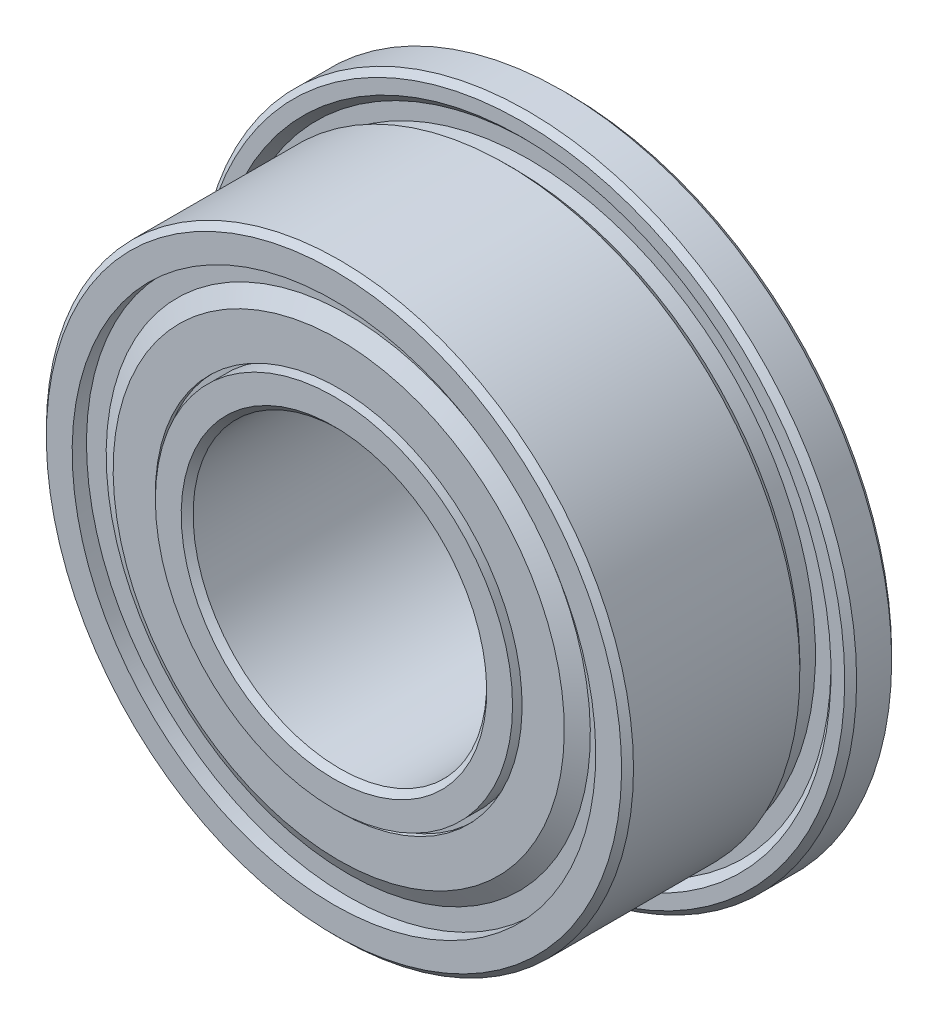
SolidWorks part; units mm, degrees
ref_plane "Front Plane" through (0, 0, 0) normal (0, 0, 1) x (1, 0, 0)
ref_plane "Top Plane" through (0, 0, 0) normal (0, 1, 0) x (1, 0, 0)
ref_plane "Right Plane" through (0, 0, 0) normal (1, 0, 0) x (0, 0, -1)
sketch "Sketch1" plane through (0, 0, 0) normal (1, 0, 0) x (0, 0, -1)
  line L0 (0, 5) -> (0, -5) construction
  line L1 (-2, 5) -> (2, 5) construction
  line L2 (0, 0) -> (2, 0) construction
  line L3 (2, 5.6) -> (2, -5.6) construction
  line L4 (2, -5.6) -> (1.2, -5.6) construction
  line L5 (2, 2.5) -> (0, 2.5) construction
  line L6 (2, 2.5) -> (2, -2.5) construction
  dimension "OD" = 10
  dimension "Width" = 4
  dimension "Flange Thickness" = 0.8
  dimension "ID" = 5
  dimension "Flange OD" = 11.2
sketch "Sketch2" plane through (0, 0, 0) normal (1, 0, 0) x (0, 0, -1)
  line L0 (2, 5.6) -> (1.2, 5.6)
  line L1 (1.2, 5.6) -> (1.2, 5.2652)
  line L2 (0.9348, 5) -> (-2, 5)
  line L3 (-2, 5) -> (-2, 4.1875)
  line L4 (-2, 4.1875) -> (-0.4106, 4.1875)
  line L5 (2, 5.6) -> (2, -5.6) construction
  line L6 (2, 4.1875) -> (2, 5.6)
  line L7 (2, 2.5) -> (-2, 2.5)
  line L8 (-2, 2.5) -> (-2, 3.3125)
  line L9 (-2, 3.3125) -> (-0.4106, 3.3125)
  line L10 (2, 3.3125) -> (2, 2.5)
  line L11 (0, 5) -> (0, 2.5) construction
  line L12 (-0.6, 3.75) -> (0.6, 3.75) construction
  line L13 (0.4106, 4.1875) -> (2, 4.1875)
  line L14 (0.4106, 3.3125) -> (2, 3.3125)
  line L15 (1.2, 5.2652) -> (1.3326, 5.1326)
  line L16 (1.3326, 5.1326) -> (1.3326, 4.8674)
  line L17 (1.3326, 4.8674) -> (1.0674, 4.8674)
  line L18 (1.0674, 4.8674) -> (0.9348, 5)
  line L19 (1.2, 5) -> (1.3326, 4.8674) construction
  line L20 (1.3326, 5.1326) -> (1.0674, 4.8674) construction
  line L21 (0.9348, 5) -> (1.2, 5) construction
  line L22 (1.2, 5) -> (1.2, 5.2652) construction
  line L23 (-2, 0) -> (2, 0) construction
  circle A0 centre (0, 3.75) radius 0.6 construction
  arc A1 (-0.4106, 4.1875) -> (0.4106, 4.1875) centre (0, 3.75) cw
  arc A2 (-0.4106, 3.3125) -> (0.4106, 3.3125) centre (0, 3.75) ccw
  dimension "Ball Dia." = 1.2
  dimension "D2" = 135
  dimension "D3" = 0.375
  dimension "Race Thikness" = 0.8125
  dimension "D4" = 0.875
revolve "Revolve1" add sketch "Sketch2" angle 360 about L2
fillet "Fillet1" radius 0.1016 3 edges at (0, -5.6, -2) (0, -5.6, -1.2) (0, -5, 2) profile chamfer
sketch "Sketch3" plane through (0, 0, 0) normal (0, 0, 1) x (1, 0, 0)
  line L0 (-2.5, 0) -> (2.5, 0) construction
  line L1 (-5, 0) -> (5, 0) construction
  point P5 (0, 0)
  dimension "ID2" = 5
  dimension "OD2" = 10
fillet "Fillet2" radius 0.1016 2 edges at (0, -2.5, -2) (0, -2.5, 2) profile chamfer
sketch "Sketch7" plane through (0, 0, 0) normal (0, 0, 1) x (1, 0, 0)
  line L0 (0, 4.35) -> (0, 3.15)
  line L1 (0, 5.6) -> (0, -5.6) construction
  line L2 (-0.7051, 4.35) -> (0, 0) construction
  line L3 (0, 0) -> (0.7051, 4.35) construction
  line L4 (0.7051, 4.35) -> (-0.7051, 4.35) construction
  circle A0 centre (0, 3.75) radius 0.6 construction
  circle A1 centre (0, 0) radius 4.35 construction
  circle A2 centre (0, 0) radius 3.15 construction
  arc A4 (0, 4.35) -> (0, 3.15) centre (0, 3.75) ccw
  dimension "D1" = 18.414
revolve "Revolve3" add sketch "Sketch7" angle 360 about L0
pattern_circular "CirPattern3" count 16 over 360 about axis through (0, 0, 0) along (0, 0, 1) of bodies 107
sketch "Sketch8" plane through (0, 0, 0) normal (1, 0, 0) x (0, 0, -1)
  line L1 (-2, 4.1875) -> (-1.675, 4.1875)
  line L2 (-2, 4.1875) -> (-2, 4.4583)
  line L3 (-2, 4.4583) -> (-1.675, 4.4583)
  line L4 (-1.675, 4.1875) -> (-1.675, 4.4583)
  line L5 (2, 4.1875) -> (1.675, 4.1875)
  line L6 (2, 4.1875) -> (2, 4.4583)
  line L7 (2, 4.4583) -> (1.675, 4.4583)
  line L8 (1.675, 4.1875) -> (1.675, 4.4583)
  line L9 (2, 3.3125) -> (1.675, 3.3125)
  line L10 (2, 3.3125) -> (2, 3.0417)
  line L11 (2, 3.0417) -> (1.675, 3.0417)
  line L12 (1.675, 3.3125) -> (1.675, 3.0417)
  line L13 (-2, 3.3125) -> (-1.675, 3.3125)
  line L14 (-2, 3.3125) -> (-2, 3.0417)
  line L15 (-2, 3.0417) -> (-1.675, 3.0417)
  line L16 (-1.675, 3.3125) -> (-1.675, 3.0417)
  dimension "D1" = 0.2708
  dimension "D2" = 0.325
revolve "Cut-Revolve1" cut sketch "Sketch8" angle 360 about L2
sketch "Sketch9" plane through (0, 0, 0) normal (1, 0, 0) x (0, 0, -1)
  line L0 (-1.675, 4.4583) -> (-1.675, 4.1012)
  line L1 (-1.675, 4.1012) -> (-1.8375, 3.8197)
  line L2 (-1.8375, 3.8197) -> (-1.8375, 3.1229)
  line L3 (1.8375, 3.1229) -> (1.8375, 3.0417) construction
  line L4 (1.675, 4.4583) -> (1.675, 4.1012)
  line L5 (1.675, 4.1012) -> (1.8375, 3.8197)
  line L6 (1.8375, 3.8197) -> (1.8375, 3.1229)
  line L7 (2, 3.0417) -> (1.675, 3.0417) construction
  line L8 (-1.7563, 4.4583) -> (-1.7563, 4.123)
  line L9 (-1.7563, 4.123) -> (-1.9188, 3.8415)
  line L10 (-1.9188, 3.8415) -> (-1.9188, 3.1229)
  line L11 (-1.675, 4.4583) -> (-1.7563, 4.4583)
  line L12 (-1.8375, 3.1229) -> (-1.9188, 3.1229)
  line L13 (1.7563, 4.4583) -> (1.7563, 4.123)
  line L14 (1.7563, 4.123) -> (1.9188, 3.8415)
  line L15 (1.9188, 3.8415) -> (1.9188, 3.1229)
  line L16 (1.675, 4.4583) -> (1.7563, 4.4583)
  line L17 (1.8375, 3.1229) -> (1.9188, 3.1229)
  line L18 (-1.675, 4.1012) -> (-1.675, 2.5308) construction
  line L19 (1.675, 4.1012) -> (1.675, 4.4583) construction
  line L20 (-1.675, 3.0417) -> (-2, 3.0417) construction
  line L22 (-1.8375, 3.1229) -> (-1.8375, 3.0417) construction
  dimension "D2" = 150
  dimension "D1" = 150
  dimension "D5" = 0.325
  dimension "D3" = 0.0813
  dimension "D4" = 0.0813
  dimension "D6" = 0.3571
revolve "Revolve4" add sketch "Sketch9" angle 360 about L2
equation "\"D1@Fillet1\"=\"Race Thikness@Sketch2\"/8"
equation "\"ID2@Sketch3\" = \"ID@Sketch1\""
equation "\"OD2@Sketch3\" = \"OD@Sketch1\""
equation "\"D1@Fillet2\"=\"Race Thikness@Sketch2\"/8"
equation "\"D1@CirPattern3\"=360/\"D1@Sketch7\"-4"
equation "\"D1@Sketch8\"=\"Race Thikness@Sketch2\"/3"
equation "\"D2@Sketch8\"=\"Race Thikness@Sketch2\"/2.5"
equation "\"D3@Sketch9\"=\"D5@Sketch9\"/4"
equation "\"D4@Sketch9\"=\"D5@Sketch9\"/4"
equation "\"D1@Sketch9\"=\"D2@Sketch9\""
equation "\"Ball Dia.@Sketch2\" = \"D1@Sketch2\"*.5"
equation "\"D4@Sketch2\"=((\"OD@Sketch1\"-\"ID@Sketch1\")/2)*.35"
